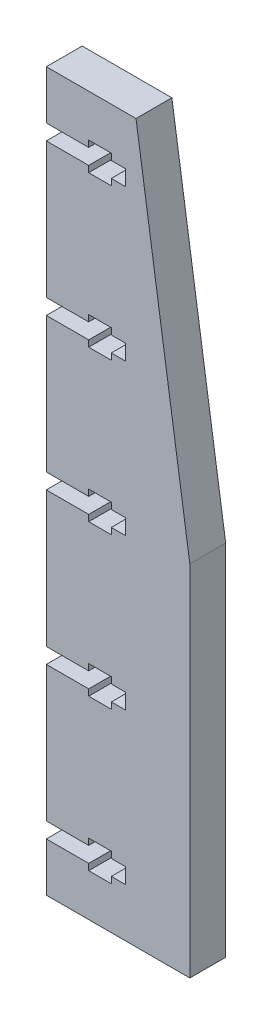
SolidWorks part; units mm, degrees
material "6061 Alloy"
ref_plane "Front Plane" through (0, 0, 0) normal (0, 0, 1) x (1, 0, 0)
ref_plane "Top Plane" through (0, 0, 0) normal (0, 1, 0) x (1, 0, 0)
ref_plane "Right Plane" through (0, 0, 0) normal (1, 0, 0) x (0, 0, -1)
sketch "Sketch1" plane through (0, 0, 0) normal (1, 0, 0) x (0, 0, -1)
  line L1 (-3.175, -63.5) -> (3.175, -63.5)
  line L2 (-3.175, -63.5) -> (-3.175, 63.5)
  line L3 (-3.175, 63.5) -> (3.175, 63.5)
  line L4 (3.175, -63.5) -> (3.175, 63.5)
  line L5 (-3.175, -63.5) -> (3.175, 63.5) construction
  line L6 (-3.175, 63.5) -> (3.175, -63.5) construction
  point P0 (0, 0)
  dimension "D1" = 6.35
  dimension "D2" = 127
extrude "Boss-Extrude1" add sketch "Sketch1" along normal blind 25.4
hole_wizard "M2.5x0.45 Tapped Hole1" [suppressed] positions "Sketch2" profile "Sketch3" tap size "M2.5x0.45" standard "ANSI Metric"
sketch "Sketch2" plane through (0, 0, 0) normal (-1, 0, 0) x (0, 0, 1)
  line L0 (0, -53.5) -> (0, -26.75)
  line L1 (0, -26.75) -> (0, 0)
  line L2 (0, 0) -> (0, 26.75)
  line L3 (0, 26.75) -> (0, 53.5)
  line L5 (-3.175, 63.5) -> (3.175, 63.5) construction
  point P0 (0, 53.5)
  point P2 (0, 26.75)
  point P4 (0, 0)
  point P7 (0, -26.75)
  point P9 (0, -53.5)
  dimension "D1" = 10
sketch "Sketch3" plane through (0, 53.5, 0) normal (0, 1, 0) x (0, 0, 1)
  line L0 (0, 0) -> (0, 6.9659)
  line L1 (0, 6.9659) -> (1.025, 6.35)
  line L2 (1.025, 6.35) -> (1.025, 0)
  line L5 (1.025, 0) -> (0, 0)
  line L10 (0, 6.9659) -> (-1.025, 6.35) construction
  line L11 (0, -6.35) -> (0, 107.95) construction
  dimension "Tap Drill Dia." = 2.05
  dimension "Tap Drill Depth" = 6.35
  dimension "Drill Angle" = 118
cosmetic thread "Hole Thread1" [suppressed] parameters "D1"=5, "D2"=2.5
cosmetic thread "Hole Thread2" [suppressed] parameters "D1"=5, "D2"=2.5
cosmetic thread "Hole Thread3" [suppressed] parameters "D1"=5, "D2"=2.5
cosmetic thread "Hole Thread4" [suppressed] parameters "D1"=5, "D2"=2.5
cosmetic thread "Hole Thread5" [suppressed] parameters "D1"=5, "D2"=2.5
sketch "Sketch4" plane through (0, 0, 3.175) normal (0, 0, 1) x (1, 0, 0)
  line L0 (15.875, 63.5) -> (25.4, 0)
  line L2 (25.4, 63.5) -> (25.4, -63.5) construction
  line L3 (14, -1.375) -> (11.5, -1.375)
  line L4 (14, -1.375) -> (14, 1.375)
  line L5 (0, -1.375) -> (0, 1.375)
  line L6 (14, 1.375) -> (11.5, 1.375)
  line L7 (11.5, -2.5) -> (7.5, -2.5)
  line L8 (11.5, -2.5) -> (11.5, -1.375)
  line L9 (7.5, -2.5) -> (7.5, -1.375)
  line L10 (11.5, 2.5) -> (7.5, 2.5)
  line L11 (0, 63.5) -> (0, -63.5) construction
  line L12 (14, -28.125) -> (11.5, -28.125)
  line L13 (14, -28.125) -> (14, -25.375)
  line L14 (0, -28.125) -> (0, -25.375)
  line L15 (14, -25.375) -> (11.5, -25.375)
  line L16 (11.5, -29.25) -> (7.5, -29.25)
  line L17 (11.5, -29.25) -> (11.5, -28.125)
  line L18 (7.5, -29.25) -> (7.5, -28.125)
  line L19 (11.5, -24.25) -> (7.5, -24.25)
  line L20 (14, -54.875) -> (11.5, -54.875)
  line L21 (14, -54.875) -> (14, -52.125)
  line L22 (0, -54.875) -> (0, -52.125)
  line L23 (14, -52.125) -> (11.5, -52.125)
  line L24 (11.5, -56) -> (7.5, -56)
  line L25 (11.5, -56) -> (11.5, -54.875)
  line L26 (7.5, -56) -> (7.5, -54.875)
  line L27 (11.5, -51) -> (7.5, -51)
  line L28 (14, 25.375) -> (11.5, 25.375)
  line L29 (14, 25.375) -> (14, 28.125)
  line L30 (0, 25.375) -> (0, 28.125)
  line L31 (14, 28.125) -> (11.5, 28.125)
  line L32 (11.5, 24.25) -> (7.5, 24.25)
  line L33 (11.5, 24.25) -> (11.5, 25.375)
  line L34 (7.5, 24.25) -> (7.5, 25.375)
  line L35 (11.5, 29.25) -> (7.5, 29.25)
  line L36 (14, 52.125) -> (11.5, 52.125)
  line L37 (14, 52.125) -> (14, 54.875)
  line L38 (0, 52.125) -> (0, 54.875)
  line L39 (14, 54.875) -> (11.5, 54.875)
  line L40 (11.5, 51) -> (7.5, 51)
  line L41 (11.5, 51) -> (11.5, 52.125)
  line L42 (7.5, 51) -> (7.5, 52.125)
  line L43 (11.5, 56) -> (7.5, 56)
  line L44 (7.5, -54.875) -> (7.5, -52.125) construction
  line L45 (7.5, -52.125) -> (7.5, -51)
  line L46 (11.5, -54.875) -> (11.5, -52.125) construction
  line L47 (11.5, -52.125) -> (11.5, -51)
  line L48 (11.5, -52.125) -> (7.5, -52.125) construction
  line L49 (7.5, -52.125) -> (0, -52.125)
  line L50 (11.5, -54.875) -> (7.5, -54.875) construction
  line L51 (7.5, -54.875) -> (0, -54.875)
  line L52 (7.5, -28.125) -> (7.5, -25.375) construction
  line L53 (7.5, -25.375) -> (7.5, -24.25)
  line L54 (11.5, -28.125) -> (7.5, -28.125) construction
  line L55 (7.5, -28.125) -> (0, -28.125)
  line L56 (11.5, -25.375) -> (7.5, -25.375) construction
  line L57 (7.5, -25.375) -> (0, -25.375)
  line L58 (11.5, -28.125) -> (11.5, -25.375) construction
  line L59 (11.5, -25.375) -> (11.5, -24.25)
  line L60 (7.5, -1.375) -> (7.5, 1.375) construction
  line L61 (7.5, 1.375) -> (7.5, 2.5)
  line L62 (11.5, 1.375) -> (7.5, 1.375) construction
  line L63 (7.5, 1.375) -> (0, 1.375)
  line L64 (11.5, -1.375) -> (11.5, 1.375) construction
  line L65 (11.5, 1.375) -> (11.5, 2.5)
  line L66 (11.5, -1.375) -> (7.5, -1.375) construction
  line L67 (7.5, -1.375) -> (0, -1.375)
  line L68 (7.5, 25.375) -> (7.5, 28.125) construction
  line L69 (7.5, 28.125) -> (7.5, 29.25)
  line L70 (11.5, 28.125) -> (7.5, 28.125) construction
  line L71 (7.5, 28.125) -> (0, 28.125)
  line L72 (11.5, 25.375) -> (11.5, 28.125) construction
  line L73 (11.5, 28.125) -> (11.5, 29.25)
  line L74 (11.5, 25.375) -> (7.5, 25.375) construction
  line L75 (7.5, 25.375) -> (0, 25.375)
  line L76 (11.5, 52.125) -> (7.5, 52.125) construction
  line L77 (7.5, 52.125) -> (0, 52.125)
  line L78 (11.5, 52.125) -> (11.5, 54.875) construction
  line L79 (11.5, 54.875) -> (11.5, 56)
  line L80 (7.5, 52.125) -> (7.5, 54.875) construction
  line L81 (7.5, 54.875) -> (7.5, 56)
  line L82 (11.5, 54.875) -> (7.5, 54.875) construction
  line L83 (7.5, 54.875) -> (0, 54.875)
  point P16 (0, 0)
  point P18 (0, 0)
  line M1 (0, 63.5) -> (0, -63.5)
  line M3 (25.4, -63.5) -> (25.4, 63.5)
  line M4 (25.4, 63.5) -> (0, 63.5)
  dimension "D1" = 14
  dimension "D2" = 2.75
  dimension "D3" = 5
  dimension "D4" = 4
  dimension "D5" = 1.125
  dimension "D6" = 2.5
  dimension "D9" = 9.525
  dimension "D7" = 3
  dimension "D8" = 3
extrude "Cut-Extrude1" cut sketch "Sketch4" against normal through all and the other way through all contours L81 L83 L77 L42 L40 L41 L36 L37 L39 L79 L43 M1 | L0 M4 M3 | L75 L34 L32 L33 L28 L29 L31 L73 L35 L69 L71 M1 | L67 L9 L7 L8 L3 L4 L6 L65 L10 L61 L63 M1 | L15 L59 L19 L53 L57 L55 L18 L16 L17 L12 L13 M1 | L51 L26 L24 L25 L20 L21 L23 L47 L27 L45 L49 M1
